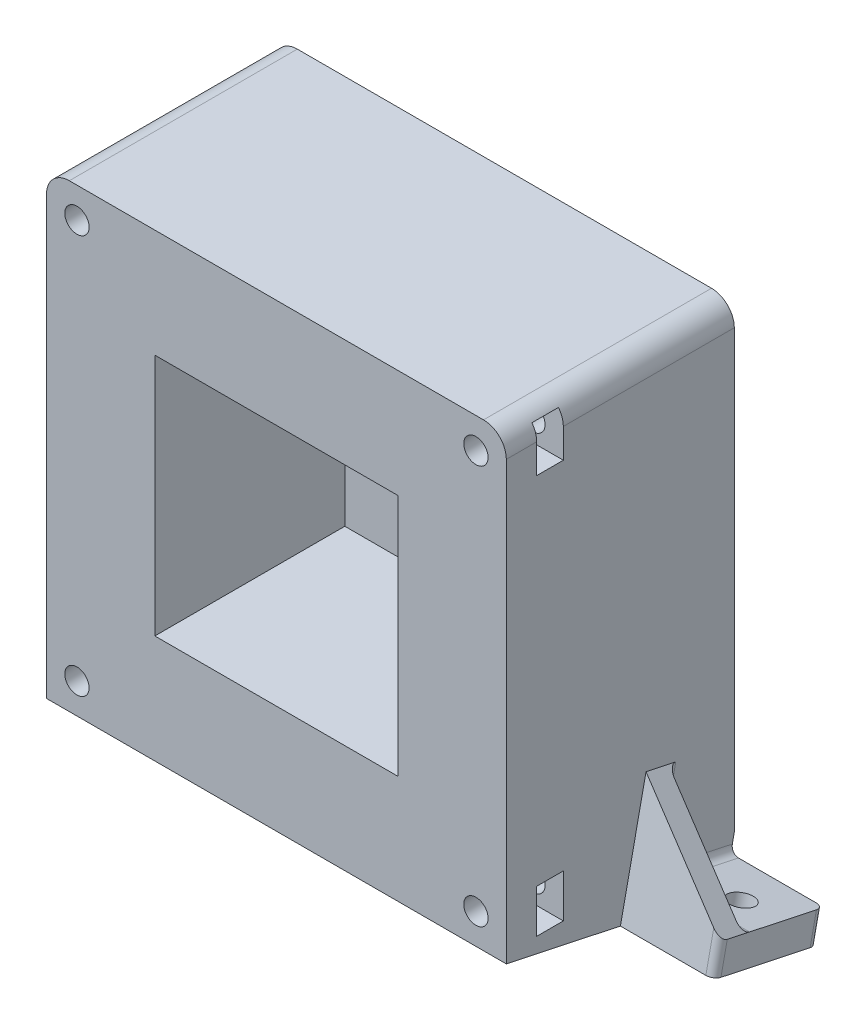
SolidWorks part; units mm, degrees
material "ABS"
ref_plane "Front Plane" through (0, 0, 0) normal (0, 0, 1) x (1, 0, 0)
ref_plane "Top Plane" through (0, 0, 0) normal (0, 1, 0) x (1, 0, 0)
ref_plane "Right Plane" through (0, 0, 0) normal (1, 0, 0) x (0, 0, -1)
sketch "ｽｹｯﾁ1" plane through (0, 0, 0) normal (0, 0, 1) x (1, 0, 0)
  line L1 (16, -16) -> (-16, -16)
  line L2 (16, -16) -> (16, 16)
  line L3 (16, 16) -> (-16, 16)
  line L4 (30.25, -27.25) -> (30.25, 27.25)
  line L5 (-27.25, -30.25) -> (27.25, -30.25)
  line L6 (-30.25, 27.25) -> (-30.25, -27.25)
  line L7 (27.25, 30.25) -> (-27.25, 30.25)
  line L8 (30.25, -30.25) -> (30.25, 27.25)
  line L9 (-30.25, -30.25) -> (30.25, -30.25)
  line L10 (-30.25, 27.25) -> (-30.25, -30.25)
  line L11 (27.25, 30.25) -> (-27.25, 30.25)
  line L12 (-16, -16) -> (-16, 16)
  line L13 (16, -16) -> (-16, 16) construction
  line L14 (16, 16) -> (-16, -16) construction
  circle A0 centre (-26.25, 26.25) radius 1.6 construction
  circle A1 centre (-26.25, -26.25) radius 1.6 construction
  circle A2 centre (26.25, -26.25) radius 1.6 construction
  circle A3 centre (26.25, 26.25) radius 1.6 construction
  circle A4 centre (-26.25, 26.25) radius 1.6
  circle A5 centre (-26.25, -26.25) radius 1.6
  circle A6 centre (26.25, -26.25) radius 1.6
  circle A7 centre (26.25, 26.25) radius 1.6
  arc A12 (-27.25, 30.25) -> (-30.25, 27.25) centre (-27.25, 27.25) ccw
  arc A13 (-27.25, 30.25) -> (-30.25, 27.25) centre (-27.25, 27.25) ccw
  arc A14 (30.25, 27.25) -> (27.25, 30.25) centre (27.25, 27.25) ccw
  arc A15 (30.25, 27.25) -> (27.25, 30.25) centre (27.25, 27.25) ccw
  arc A22 (-30.25, -27.25) -> (-27.25, -30.25) centre (-27.25, -27.25) ccw
  arc A24 (27.25, -30.25) -> (30.25, -27.25) centre (27.25, -27.25) ccw
  point P16 (0, 0)
  point P21 (32.1247, -30.25)
  point P24 (30.25, -33.7738)
  point P26 (-30.25, -33.8303)
  point P28 (-34.6865, -30.25)
  dimension "D2" = 32
  dimension "D1" = 0
extrude "ﾎﾞｽ - 押し出し1" add sketch "ｽｹｯﾁ1" against normal blind 30
sketch "ｽｹｯﾁ3" plane through (0, 0, -30) normal (0, 0, -1) x (-1, 0, 0)
  line L0 (16, 16) -> (16, -16) construction
  line L1 (16, -16) -> (-16, -16) construction
  line L2 (-16, -16) -> (-16, 16) construction
  line L3 (-16, 16) -> (16, 16) construction
  line L4 (16, 16) -> (16, -16)
  line L5 (16, -16) -> (-16, -16)
  line L6 (-16, -16) -> (-16, 16)
  line L7 (-16, 16) -> (16, 16)
extrude "ﾎﾞｽ - 押し出し2" add sketch "ｽｹｯﾁ3" against normal blind 5
sketch "ｽｹｯﾁ4" plane through (0, 0, -30) normal (0, 0, -1) x (-1, 0, 0)
  circle A0 centre (0, 0) radius 6.35
  dimension "D1" = 12.7
extrude "ｶｯﾄ - 押し出し1" cut sketch "ｽｹｯﾁ4" against normal through all
sketch "ｽｹｯﾁ5" plane through (0, 0, -25) normal (0, 0, 1) x (1, 0, 0)
  circle A0 centre (0, 0) radius 10
  dimension "D1" = 20
extrude "ｶｯﾄ - 押し出し2" cut sketch "ｽｹｯﾁ5" against normal offset from surface (3 mm away) 2 up to face at (-6.35, 0, -30)
ref_plane "平面2" through (0, 0, -4) normal (0, 0, 1) x (1, 0, 0)
sketch "ｽｹｯﾁ10" plane through (0, 0, -4) normal (0, 0, 1) x (1, 0, 0)
  line L0 (27.8954, -23.4) -> (30.25, -23.4)
  line L1 (27.8954, -23.4) -> (24.6046, -23.4)
  line L2 (24.6046, -23.4) -> (22.9591, -26.25)
  line L3 (22.9591, -26.25) -> (24.6046, -29.1)
  line L4 (24.6046, -29.1) -> (27.8954, -29.1)
  line L5 (27.8954, -29.1) -> (29.5409, -26.25) construction
  line L6 (29.5409, -26.25) -> (27.8954, -23.4) construction
  line L7 (30.25, -23.4) -> (30.25, -29.1)
  line L8 (30.25, -29.1) -> (27.8954, -29.1)
  line L9 (30.25, -30.25) -> (30.25, 27.25) construction
  line L10 (26.25, 0) -> (0, 0) construction
  line L11 (0, 0) -> (0, 29.1387) construction
  line L12 (-29.5409, -26.25) -> (-27.8954, -23.4) construction
  line L13 (-27.8954, -29.1) -> (-29.5409, -26.25) construction
  line L14 (-30.25, -29.1) -> (-27.8954, -29.1)
  line L15 (-30.25, -23.4) -> (-30.25, -29.1)
  line L16 (-24.6046, -29.1) -> (-27.8954, -29.1)
  line L17 (-22.9591, -26.25) -> (-24.6046, -29.1)
  line L18 (-24.6046, -23.4) -> (-22.9591, -26.25)
  line L19 (-27.8954, -23.4) -> (-24.6046, -23.4)
  line L20 (-27.8954, -23.4) -> (-30.25, -23.4)
  line L21 (-27.8954, 29.1) -> (-29.5409, 26.25) construction
  line L22 (-29.5409, 26.25) -> (-27.8954, 23.4) construction
  line L23 (29.5409, 26.25) -> (27.8954, 23.4) construction
  line L24 (27.8954, 29.1) -> (29.5409, 26.25) construction
  line L25 (-27.8954, 23.4) -> (-30.25, 23.4)
  line L26 (-27.8954, 23.4) -> (-24.6046, 23.4)
  line L27 (-24.6046, 23.4) -> (-22.9591, 26.25)
  line L28 (-22.9591, 26.25) -> (-24.6046, 29.1)
  line L29 (-24.6046, 29.1) -> (-27.8954, 29.1)
  line L30 (-30.25, 23.4) -> (-30.25, 29.1)
  line L31 (-30.25, 29.1) -> (-27.8954, 29.1)
  line L32 (30.25, 29.1) -> (27.8954, 29.1)
  line L33 (30.25, 23.4) -> (30.25, 29.1)
  line L34 (24.6046, 29.1) -> (27.8954, 29.1)
  line L35 (22.9591, 26.25) -> (24.6046, 29.1)
  line L36 (24.6046, 23.4) -> (22.9591, 26.25)
  line L37 (27.8954, 23.4) -> (24.6046, 23.4)
  line L38 (27.8954, 23.4) -> (30.25, 23.4)
  circle A0 centre (26.25, -26.25) radius 2.85 construction
  circle A1 centre (-26.25, -26.25) radius 2.85 construction
  circle A2 centre (-26.25, 26.25) radius 2.85 construction
  circle A3 centre (26.25, 26.25) radius 2.85 construction
  dimension "D1" = 5.7
extrude "ｶｯﾄ - 押し出し3" cut sketch "ｽｹｯﾁ10" against normal blind 3.5
sketch "ｽｹｯﾁ11" plane through (0, 0, -30) normal (0, 0, -1) x (-1, 0, 0)
  circle A0 centre (26.25, 26.25) radius 1.6 construction
  circle A1 centre (-26.25, 26.25) radius 1.6 construction
  circle A2 centre (26.25, -26.25) radius 1.6 construction
  circle A3 centre (-26.25, -26.25) radius 1.6 construction
  circle A4 centre (26.25, 26.25) radius 1.6
  circle A5 centre (-26.25, 26.25) radius 1.6
  circle A6 centre (26.25, -26.25) radius 1.6
  circle A7 centre (-26.25, -26.25) radius 1.6
sketch "ｽｹｯﾁ13" plane through (-30.25, 0, 0) normal (-1, 0, 0) x (0, 0, 1)
  line L0 (-30, -30.25) -> (-28.7032, -36.351)
  line L1 (-28.7032, -36.351) -> (0, -30.25)
  line L2 (-30, -30.25) -> (0, -30.25) construction
  line L3 (-30, -30.25) -> (0, -30.25)
  dimension "D1" = 12
extrude "ﾎﾞｽ - 押し出し3" add sketch "ｽｹｯﾁ13" against normal up to surface (60.5 mm away) up to face at (30.25, -26.25, -5.75)
sketch "ｽｹｯﾁ14" plane through (0, -28.9424, 6.1519) normal (0, -0.9781, 0.2079) x (1, 0, 0)
  line L0 (-30.25, -35.6338) -> (-30.25, -6.2893) construction
  line L1 (-30.25, -21.6338) -> (-42.5, -21.6338)
  line L2 (-30.25, -21.6338) -> (-30.25, -35.6338)
  line L3 (-30.25, -35.6338) -> (-42.5, -35.6338)
  line L4 (-42.5, -21.6338) -> (-42.5, -35.6338)
  line L5 (-30.25, -21.6338) -> (-42.5, -35.6338) construction
  line L6 (-30.25, -35.6338) -> (-42.5, -21.6338) construction
  line L7 (0, 0) -> (0, -40.7898) construction
  line L8 (-37.5, -29.6338) -> (0, -29.6338) construction
  line L9 (30.25, -35.6338) -> (-30.25, -35.6338) construction
  circle A0 centre (-37.5, -29.6338) radius 1.6
  point P4 (-36.375, -28.6338)
  point P15 (-36.375, -28.9262)
  point P17 (-51.0606, -23.1182)
  dimension "D1" = 3.2
  dimension "D2" = 6
  dimension "D4" = 5
  dimension "D3" = 75
  dimension "D5" = 14
extrude "ﾎﾞｽ - 押し出し4" add sketch "ｽｹｯﾁ14" against normal blind 4
sketch "ｽｹｯﾁ16" plane through (0, -4.4979, -21.161) normal (0, 0.2079, 0.9781) x (1, 0, 0)
  line L0 (-42.5, -25.589) -> (-30.25, -13.339)
  line L1 (-30.25, 26.6545) -> (-30.25, -29.589) construction
  line L2 (-30.25, -13.339) -> (-30.25, -25.589)
  line L3 (-30.25, -25.589) -> (-42.5, -25.589)
  dimension "D1" = 45
extrude "ﾎﾞｽ - 押し出し5" add sketch "ｽｹｯﾁ16" against normal blind 3
mirror "ﾐﾗｰ1" about plane through (0, 0, 0) normal (1, 0, 0) of "ﾎﾞｽ - 押し出し5", "ﾎﾞｽ - 押し出し4"
fillet "ﾌｨﾚｯﾄ1" radius 1 10 edges at (-42.5, -31.484, -15.4249) (-42.5, -34.3948, -29.119) (-30.25, -31.2949, -24.155) (-30.25, -24.1603, -20.0487) (-36.375, -30.1514, -18.7752) (42.5, -34.3948, -29.119) (42.5, -31.484, -15.4249) (30.25, -31.2949, -24.155) (36.375, -30.1514, -18.7752) (30.25, -24.1603, -20.0487)
